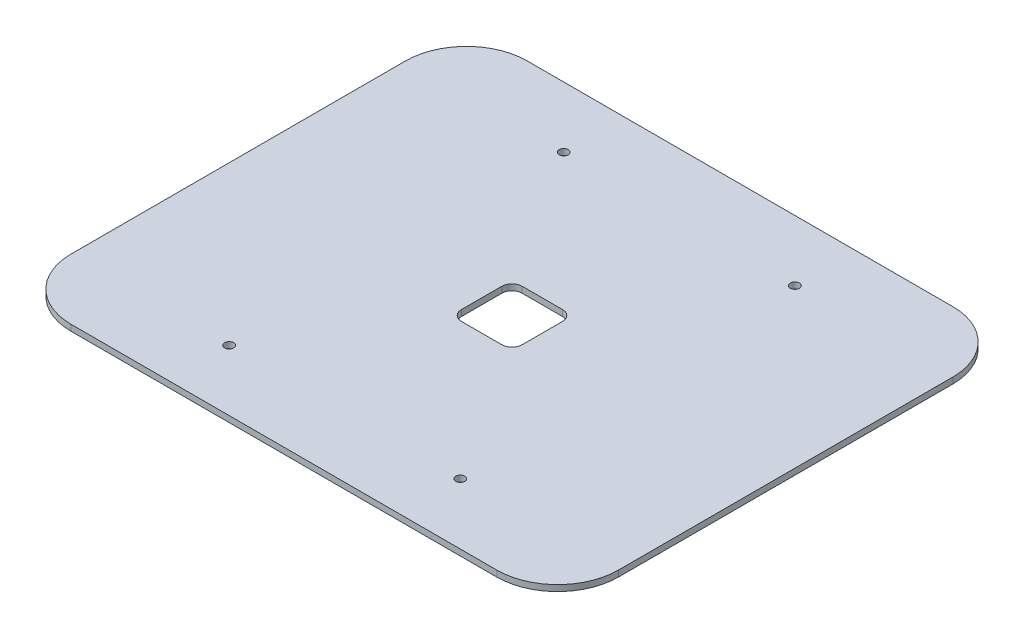
SolidWorks part; units mm, degrees
material "Cobre"
ref_plane "Plano frontal" through (0, 0, 0) normal (0, 0, 1) x (1, 0, 0)
ref_plane "Plano superior" through (0, 0, 0) normal (0, 1, 0) x (1, 0, 0)
ref_plane "Plano direito" through (0, 0, 0) normal (1, 0, 0) x (0, 0, -1)
sketch "Esboço1" plane through (0, 0, 0) normal (0, 1, 0) x (1, 0, 0)
  line L1 (-40.816, 183.1145) -> (99.184, 183.1145)
  line L2 (-60.816, 163.1145) -> (-60.816, 53.1145)
  line L3 (-40.816, 33.1145) -> (99.184, 33.1145)
  line L4 (119.184, 163.1145) -> (119.184, 53.1145)
  arc A0 (99.184, 183.1145) -> (119.184, 163.1145) centre (99.184, 163.1145) cw
  arc A1 (99.184, 33.1145) -> (119.184, 53.1145) centre (99.184, 53.1145) ccw
  arc A2 (-60.816, 53.1145) -> (-40.816, 33.1145) centre (-40.816, 53.1145) ccw
  arc A3 (-40.816, 183.1145) -> (-60.816, 163.1145) centre (-40.816, 163.1145) ccw
  dimension "D1" = 20
extrude "Ressalto-extrusão1" add sketch "Esboço1" along normal blind 2
sketch "Esboço2" plane through (0, 2, 0) normal (0, 1, 0) x (1, 0, 0)
  line L0 (81.4945, 56.1145) -> (76.184, 56.1145) construction
  line L1 (-0.816, 170.1145) -> (79.184, 170.1145) construction
  line L2 (86.9299, 160.1145) -> (76.184, 160.1145) construction
  line L3 (-6.2514, 46.1145) -> (73.7486, 46.1145) construction
  line L4 (74.184, 158.1145) -> (74.184, 58.1145) construction
  line L5 (-8.562, 160.1145) -> (-17.816, 160.1145) construction
  line L6 (-13.9974, 56.1145) -> (-17.816, 56.1145) construction
  line L7 (-15.816, 158.1145) -> (-15.816, 58.1145) construction
  line L10 (-60.816, 163.1145) -> (-60.816, 53.1145) construction
  line L11 (119.184, 53.1145) -> (119.184, 163.1145) construction
  line L12 (99.184, 183.1145) -> (-40.816, 183.1145) construction
  line L14 (-40.816, 33.1145) -> (99.184, 33.1145) construction
  arc A0 (88.8664, 162.6145) -> (79.184, 170.1145) centre (79.184, 160.1145) ccw construction
  arc A1 (73.7486, 46.1145) -> (83.431, 53.6145) centre (73.7486, 56.1145) ccw construction
  arc A2 (-10.4985, 162.6145) -> (-0.816, 170.1145) centre (-0.816, 160.1145) cw construction
  arc A3 (-15.9339, 53.6145) -> (-6.2514, 46.1145) centre (-6.2514, 56.1145) ccw construction
  arc A4 (81.4945, 56.1145) -> (83.431, 53.6145) centre (81.4945, 54.1145) cw construction
  arc A5 (74.184, 58.1145) -> (76.184, 56.1145) centre (76.184, 58.1145) ccw construction
  arc A6 (86.9299, 160.1145) -> (88.8664, 162.6145) centre (86.9299, 162.1145) ccw construction
  arc A7 (74.184, 158.1145) -> (76.184, 160.1145) centre (76.184, 158.1145) cw construction
  arc A8 (-17.816, 160.1145) -> (-15.816, 158.1145) centre (-17.816, 158.1145) cw construction
  arc A9 (-8.562, 160.1145) -> (-10.4985, 162.6145) centre (-8.562, 162.1145) cw construction
  arc A10 (-17.816, 56.1145) -> (-15.816, 58.1145) centre (-17.816, 58.1145) ccw construction
  arc A11 (-13.9974, 56.1145) -> (-15.9339, 53.6145) centre (-13.9974, 54.1145) ccw construction
  circle A12 centre (-8.816, 163.1145) radius 1.5
  circle A13 centre (67.184, 163.1145) radius 1.5
  circle A14 centre (67.184, 53.1145) radius 1.5
  circle A15 centre (-8.816, 53.1145) radius 1.5
  dimension "D1" = 10
  dimension "D2" = 2
  dimension "D9" = 7
  dimension "D10" = 7
  dimension "D11" = 3
  dimension "D12" = 7
  dimension "D13" = 7
  dimension "D14" = 3
  dimension "D15" = 7
  dimension "D16" = 7
  dimension "D17" = 3
  dimension "D18" = 7
  dimension "D3" = 100
  dimension "D4" = 45
  dimension "D5" = 100
  dimension "D6" = 45
  dimension "D7" = 13
  dimension "D8" = 13
extrude "Corte-extrusão1" cut sketch "Esboço2" against normal blind 10
sketch "Esboço3" plane through (0, 2, 0) normal (0, 1, 0) x (1, 0, 0)
  line L1 (119.184, 53.1145) -> (119.184, 163.1145) construction
  line L2 (22.5532, 118.1145) -> (35.8147, 118.1145)
  line L3 (19.184, 114.7452) -> (19.184, 101.4837)
  line L4 (22.5532, 98.1145) -> (35.8147, 98.1145)
  line L6 (39.184, 114.7452) -> (39.184, 101.4837)
  line L7 (-60.816, 163.1145) -> (-60.816, 53.1145) construction
  line L8 (99.184, 183.1145) -> (-40.816, 183.1145) construction
  line L12 (-40.816, 33.1145) -> (99.184, 33.1145) construction
  arc A0 (39.184, 114.7452) -> (35.8147, 118.1145) centre (35.8147, 114.7452) ccw
  arc A1 (35.8147, 98.1145) -> (39.184, 101.4837) centre (35.8147, 101.4837) ccw
  arc A2 (22.5532, 98.1145) -> (19.184, 101.4837) centre (22.5532, 101.4837) cw
  arc A3 (22.5532, 118.1145) -> (19.184, 114.7452) centre (22.5532, 114.7452) ccw
  point P10 (29.184, 183.1145)
  dimension "D5" = 3.3692
  dimension "D1" = 80
  dimension "D2" = 80
  dimension "D3" = 65
  dimension "D4" = 65
extrude "Corte-extrusão2" cut sketch "Esboço3" against normal blind 10
